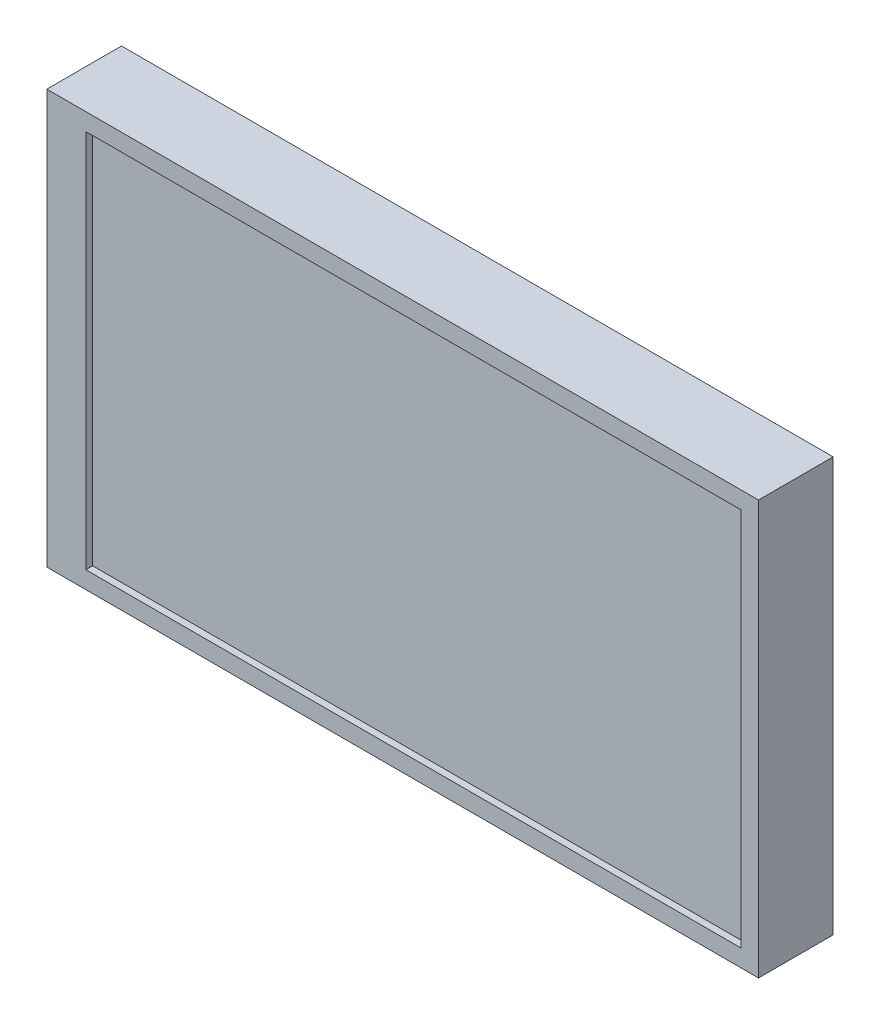
SolidWorks part; units mm, degrees
ref_plane "Front Plane" through (0, 0, 0) normal (0, 0, 1) x (1, 0, 0)
ref_plane "Top Plane" through (0, 0, 0) normal (0, 1, 0) x (1, 0, 0)
ref_plane "Right Plane" through (0, 0, 0) normal (1, 0, 0) x (0, 0, -1)
sketch "Sketch2" plane through (0, 0, 0) normal (0, 0, 1) x (1, 0, 0)
  line L1 (-254, -152.4) -> (254, -152.4)
  line L2 (-254, -152.4) -> (-254, 152.4)
  line L3 (-254, 152.4) -> (254, 152.4)
  line L4 (254, -152.4) -> (254, 152.4)
  line L5 (-254, -152.4) -> (254, 152.4) construction
  line L6 (-254, 152.4) -> (254, -152.4) construction
  point P0 (0, 0)
  dimension "D1" = 508
  dimension "D2" = 304.8
extrude "Boss-Extrude1" add sketch "Sketch2" along normal blind 55
hole_wizard "M6x1.0 Tapped Hole1" positions "Sketch3" profile "Sketch5" tap size "M6x1.0" standard "ANSI Metric"
sketch "Sketch3" plane through (0, 0, 0) normal (0, 0, -1) x (-1, 0, 0)
  line L1 (-50, -50) -> (50, -50)
  line L2 (-50, -50) -> (-50, 50)
  line L3 (-50, 50) -> (50, 50)
  line L4 (50, -50) -> (50, 50)
  line L5 (-50, -50) -> (50, 50) construction
  line L6 (-50, 50) -> (50, -50) construction
  point P2 (50, 50)
  point P35 (-50, -50)
  point P36 (-50, 50)
  point P37 (50, -50)
  dimension "D1" = 100
sketch "Sketch5" plane through (-50, 50, 0) normal (1, 0, 0) x (0, 1, 0)
  line L0 (0, 0) -> (0, 18.5022)
  line L1 (0, 18.5022) -> (2.5, 17)
  line L2 (2.5, 17) -> (2.5, 0)
  line L5 (2.5, 0) -> (0, 0)
  line L10 (0, 18.5022) -> (-2.5, 17) construction
  line L11 (0, -6.35) -> (0, 107.95) construction
  dimension "Tap Drill Dia." = 5
  dimension "Tap Drill Depth" = 17
  dimension "Drill Angle" = 118
cosmetic thread "Hole Thread1" parameters "D1"=12, "D2"=6
cosmetic thread "Hole Thread2" parameters "D1"=12, "D2"=6
cosmetic thread "Hole Thread3" parameters "D1"=12, "D2"=6
cosmetic thread "Hole Thread4" parameters "D1"=12, "D2"=6
sketch "Sketch6" plane through (0, 0, 55) normal (0, 0, 1) x (1, 0, 0)
  line L1 (-241.3, -139.7) -> (241.3, -139.7)
  line L2 (-241.3, -139.7) -> (-241.3, 139.7)
  line L3 (-241.3, 139.7) -> (241.3, 139.7)
  line L4 (241.3, -139.7) -> (241.3, 139.7)
  line L5 (-241.3, -139.7) -> (241.3, 139.7) construction
  line L6 (-241.3, 139.7) -> (241.3, -139.7) construction
  point P0 (0, 0)
  dimension "D1" = 482.6
  dimension "D2" = 279.4
extrude "Cut-Extrude1" cut sketch "Sketch6" against normal blind 5
sketch "Sketch7" plane through (-254, 0, 0) normal (-1, 0, 0) x (0, 0, 1)
  line L4 (0, 152.4) -> (0, -152.4)
  line L5 (0, -152.4) -> (55, -152.4)
  line L6 (55, -152.4) -> (55, 152.4)
  line L7 (55, 152.4) -> (0, 152.4)
  line L8 (0, 152.4) -> (0, -152.4)
  line L9 (0, -152.4) -> (55, -152.4)
  line L10 (55, -152.4) -> (55, 152.4)
  line L11 (55, 152.4) -> (0, 152.4)
  dimension "D1" = 0
extrude "Boss-Extrude2" add sketch "Sketch7" along normal blind 16
